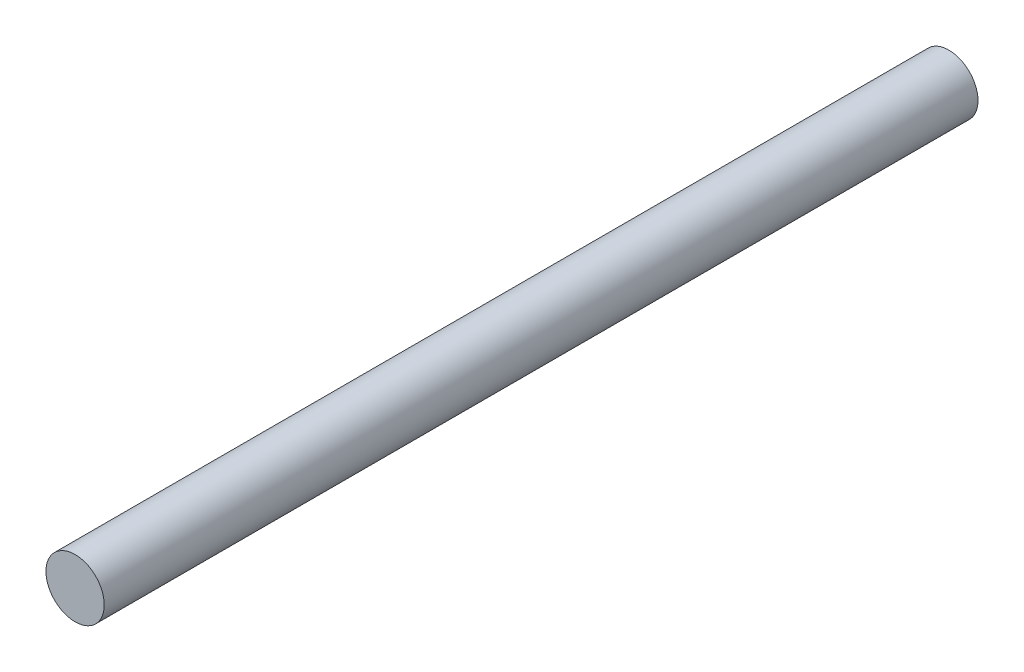
SolidWorks part; units mm, degrees
ref_plane "Front Plane" through (0, 0, 0) normal (0, 0, 1) x (1, 0, 0)
ref_plane "Top Plane" through (0, 0, 0) normal (0, 1, 0) x (1, 0, 0)
ref_plane "Right Plane" through (0, 0, 0) normal (1, 0, 0) x (0, 0, -1)
sketch "Sketch1" plane through (0, 0, 0) normal (0, 0, 1) x (1, 0, 0)
  circle A0 centre (0, 0) radius 8.89
  dimension "D1" = 17.78
extrude "Boss-Extrude1" add sketch "Sketch1" along normal blind 203.2 and the other way blind 63.2
